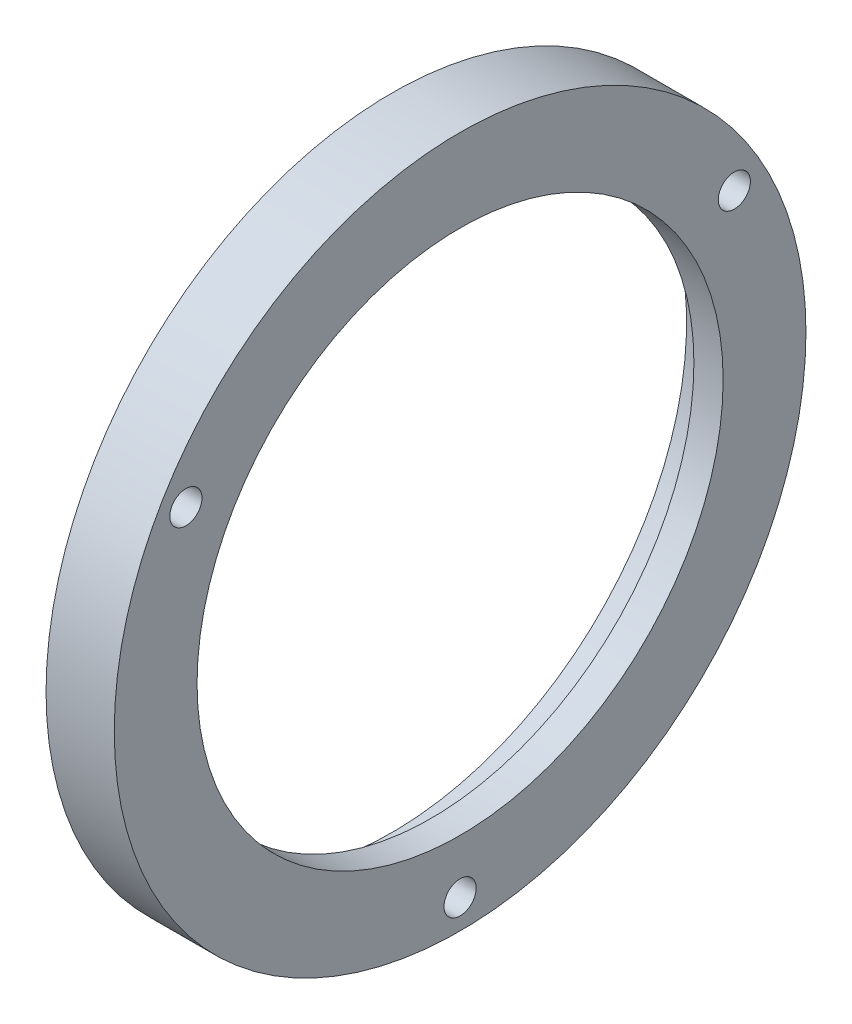
SolidWorks part; units mm, degrees
material "AISI 304"
ref_plane "Front Plane" through (0, 0, 0) normal (0, 0, 1) x (1, 0, 0)
ref_plane "Top Plane" through (0, 0, 0) normal (0, 1, 0) x (1, 0, 0)
ref_plane "Right Plane" through (0, 0, 0) normal (1, 0, 0) x (0, 0, -1)
sketch "Axial profile (mm)" plane through (0, 0, 0) normal (0, 0, 1) x (1, 0, 0)
  line L0 (-110, 0) -> (75, 0) construction
  line L1 (135.7, 30.25) -> (139.7, 30.25)
  line L2 (139.7, 30.25) -> (139.7, 27)
  line L3 (139.7, 27) -> (142.7, 27)
  line L4 (142.7, 27) -> (142.7, 35.5)
  line L5 (142.7, 35.5) -> (135.7, 35.5)
  line L6 (135.7, 35.5) -> (135.7, 30.25)
revolve "Full revolution" add sketch "Axial profile (mm)" angle 360 about L0
sketch "Sketch2" plane through (0, 0, 0) normal (1, 0, 0) x (0, 0, -1)
  circle A0 centre (-28.1458, 16.25) radius 1.65
  circle A1 centre (0, -32.5) radius 1.65
  circle A2 centre (28.1458, 16.25) radius 1.65
extrude "Axial holes" cut sketch "Sketch2" along normal through all and the other way through all
